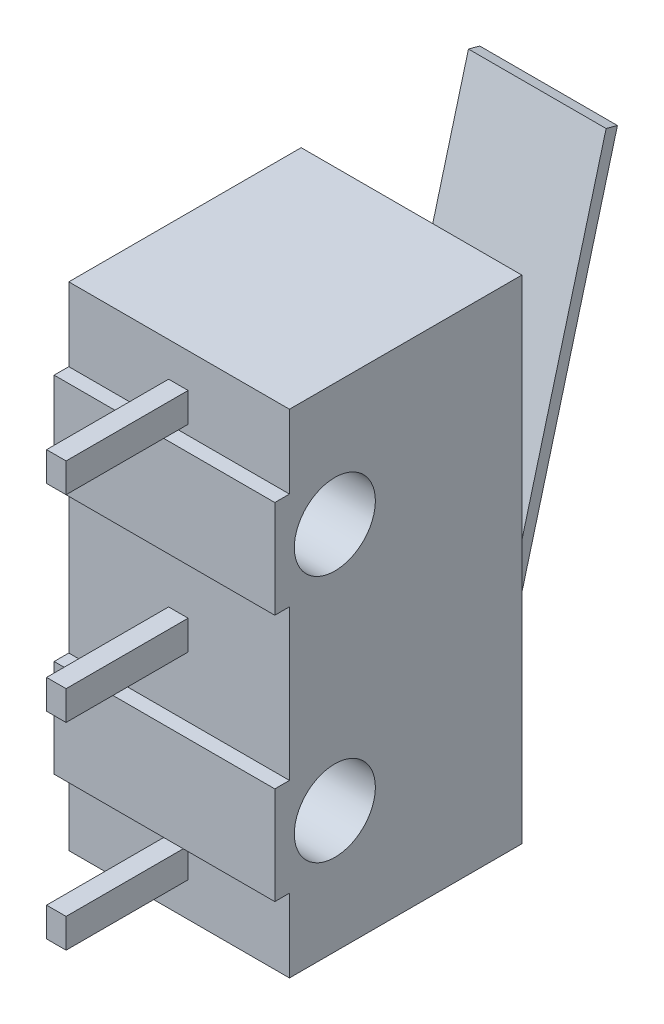
SolidWorks part; units mm, degrees
ref_plane "Front Plane" through (0, 0, 0) normal (0, 0, 1) x (1, 0, 0)
ref_plane "Top Plane" through (0, 0, 0) normal (0, 1, 0) x (1, 0, 0)
ref_plane "Right Plane" through (0, 0, 0) normal (1, 0, 0) x (0, 0, -1)
sketch "Sketch2" plane through (0, 0, 0) normal (0, 0, 1) x (1, 0, 0)
  line L1 (-2.8505, 1.7903) -> (2.8899, 1.7903)
  line L2 (-2.8505, 1.7903) -> (-2.8505, -11.024)
  line L3 (-2.8505, -11.024) -> (2.8899, -11.024)
  line L4 (2.8899, 1.7903) -> (2.8899, -11.024)
  dimension "D1" = 5.7404
  dimension "D2" = 12.8143
extrude "OG box" add sketch "Sketch2" along normal blind 6.0452
sketch "Sketch4" plane through (0, 0, 6.0452) normal (0, 0, 1) x (1, 0, 0)
  line L0 (0, 2.1565) -> (0, -11.7957) construction
  line L1 (-4.2815, -4.6168) -> (3.796, -4.6168) construction
  line L3 (-0.254, -4.2358) -> (0.254, -4.2358)
  line L4 (-0.254, -4.2358) -> (-0.254, -4.9978)
  line L5 (-0.254, -4.9978) -> (0.254, -4.9978)
  line L6 (0.254, -4.2358) -> (0.254, -4.9978)
  line L7 (-0.254, -4.2358) -> (0.254, -4.9978) construction
  line L8 (-0.254, -4.9978) -> (0.254, -4.2358) construction
  line L12 (-1.3748, -4.9978) -> (1.8935, -4.9978) construction
  line L13 (-1.4849, 0.895) -> (1.6074, 0.895) construction
  line L14 (-1.3748, -4.2358) -> (1.3537, -4.2358) construction
  line L15 (-0.254, 0.895) -> (0.254, 0.895)
  line L16 (-0.254, 0.895) -> (-0.254, 0.133)
  line L17 (-0.254, 0.133) -> (0.254, 0.133)
  line L18 (0.254, 0.895) -> (0.254, 0.133)
  line L19 (-0.965, -10.1286) -> (1.1836, -10.1286) construction
  line L21 (-0.254, -10.1286) -> (0.254, -10.1286)
  line L22 (-0.254, -10.1286) -> (-0.254, -9.3666)
  line L23 (-0.254, -9.3666) -> (0.254, -9.3666)
  line L24 (0.254, -10.1286) -> (0.254, -9.3666)
  point P5 (0, -4.6168)
  dimension "D1" = 0.508
  dimension "D2" = 0.762
  dimension "D3" = 5.8928
  dimension "D4" = 0.508
  dimension "D5" = 0.762
  dimension "D6" = 5.8928
  dimension "D7" = 0.762
  dimension "D8" = 0.508
extrude "Pins" add sketch "Sketch4" along normal blind 3.175
sketch "Clicker Outline" plane through (0, 0, 0) normal (0, 0, -1) x (-1, 0, 0)
  line L0 (-4.0921, -9.9826) -> (5.4999, -9.9826) construction
  line L1 (2.8505, -11.024) -> (-2.8899, -11.024) construction
  line L2 (0, 3.02) -> (0, -13.4308) construction
  line L3 (-1.7907, 2.8173) -> (-1.7907, -15.4872) construction
  line L4 (1.7907, 2.8173) -> (1.7907, -15.4872) construction
  dimension "D1" = 1.0414
  dimension "D2" = 1.7907
ref_plane "Plane1" through (-1.7907, 0, 0) normal (-1, 0, 0) x (0, 0, 1)
sketch "Sketch6" plane through (-1.7907, 0, 0) normal (-1, 0, 0) x (0, 0, 1)
  line L0 (0, -10.5685) -> (-3.5867, 2.8173)
  line L1 (0, 2.8173) -> (0, -15.4872) construction
  line L2 (-3.5867, 2.8173) -> (-3.2923, 2.8961)
  line L5 (-3.2923, 2.8961) -> (-2.9385, 1.5758)
  line L6 (-2.9385, 1.5758) -> (0, -9.3909)
  line L7 (0, -9.3909) -> (0, -10.5685)
  dimension "D1" = 13.3858
  dimension "D2" = 15
  dimension "D3" = 90
  dimension "D4" = 0.3048
extrude "Clicker" add sketch "Sketch6" against normal blind 3.5814
sketch "Sketch8" plane through (0, 0, 6.0452) normal (0, 0, 1) x (1, 0, 0)
  line L0 (0.254, 0.133) -> (1.6845, 0.133) construction
  line L1 (-3.2937, -0.121) -> (3.1356, -0.121) construction
  line L2 (0.254, -9.3666) -> (1.4595, -9.3666)
  line L3 (-3.2937, -9.1126) -> (3.1356, -9.1126) construction
  line L4 (-3.2937, -2.661) -> (3.2599, -2.661) construction
  line L5 (-3.2937, -6.5726) -> (3.3418, -6.5726) construction
  line L6 (2.8899, -0.121) -> (2.8899, -2.661)
  line L7 (2.8899, -11.024) -> (2.8899, 1.7903) construction
  line L8 (2.8899, -2.661) -> (-2.8505, -2.661)
  line L9 (-2.8505, 1.7903) -> (-2.8505, -11.024) construction
  line L10 (-2.8505, -2.661) -> (-2.8505, -0.121)
  line L11 (-2.8505, -0.121) -> (2.8899, -0.121)
  line L12 (-2.8505, -9.1126) -> (-2.8505, -6.5726)
  line L13 (-2.8505, -6.5726) -> (2.8899, -6.5726)
  line L14 (2.8899, -6.5726) -> (2.8899, -9.1126)
  line L15 (2.8899, -9.1126) -> (-2.8505, -9.1126)
  dimension "D1" = 0.254
  dimension "D2" = 0.254
  dimension "D3" = 2.54
  dimension "D4" = 2.54
extrude "Boss-Extrude3" add sketch "Sketch8" along normal blind 0.381 contours L15 L12 L13 L14 | L10 L11 L6 L8
sketch "Sketch9" plane through (2.8899, 0, 0) normal (1, 0, 0) x (0, 0, -1)
  line L0 (-7.1812, -1.391) -> (0.5406, -1.391) construction
  line L1 (-6.9966, -7.8426) -> (1.4638, -7.8426) construction
  line L2 (-6.4262, 1.5337) -> (-6.4262, -12.1249) construction
  line L3 (-5.9182, 2.3834) -> (-5.9182, -12.4937) construction
  line L4 (-4.8641, 2.6934) -> (-4.8641, -12.4937) construction
  circle A0 centre (-4.8641, -1.391) radius 1.0541
  circle A1 centre (-4.8641, -7.8426) radius 1.0541
  dimension "D1" = 0.508
  dimension "D2" = 1.0541
extrude "Cut-Extrude1" cut sketch "Sketch9" against normal blind 8.89
